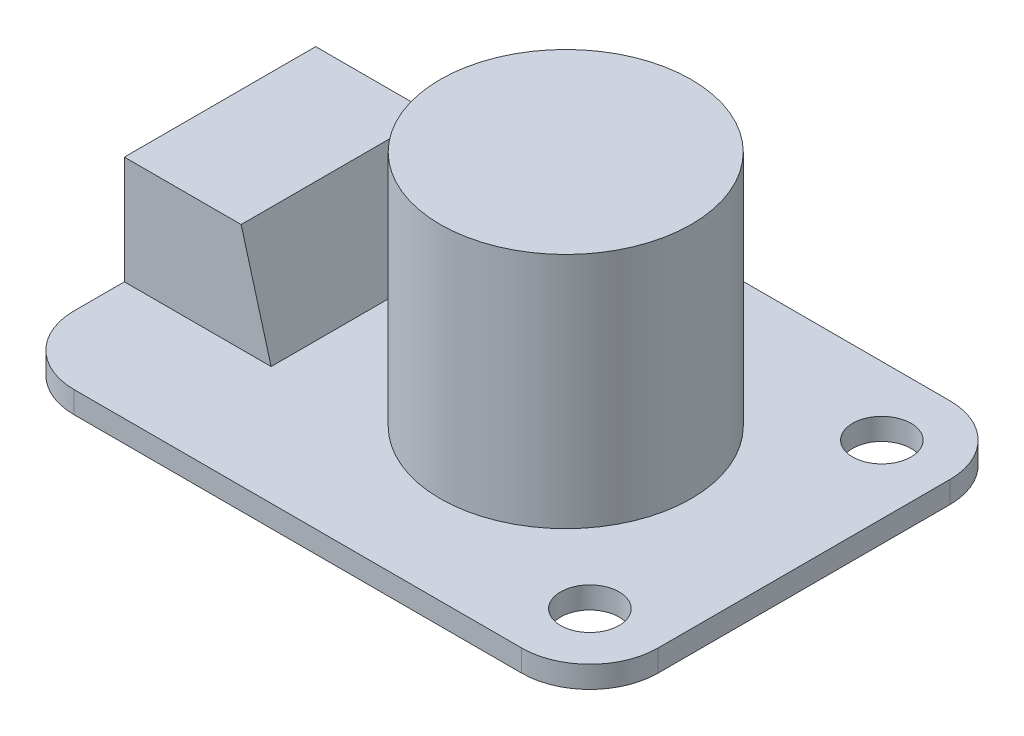
SolidWorks part; units mm, degrees
ref_plane "Front Plane" through (0, 0, 0) normal (0, 0, 1) x (1, 0, 0)
ref_plane "Top Plane" through (0, 0, 0) normal (0, 1, 0) x (1, 0, 0)
ref_plane "Right Plane" through (0, 0, 0) normal (1, 0, 0) x (0, 0, -1)
sketch "Sketch1" plane through (0, 0, 0) normal (0, 1, 0) x (1, 0, 0)
  line L0 (3.5, 0) -> (26.5, 0)
  line L1 (30, 3.5) -> (30, 18.5)
  line L2 (26.5, 22) -> (3.5, 22)
  line L3 (0, 18.5) -> (0, 3.5)
  arc A0 (3.5, 22) -> (0, 18.5) centre (3.5, 18.5) ccw
  arc A1 (3.5, 0) -> (0, 3.5) centre (3.5, 3.5) cw
  arc A2 (26.5, 0) -> (30, 3.5) centre (26.5, 3.5) ccw
  arc A3 (30, 18.5) -> (26.5, 22) centre (26.5, 18.5) ccw
  circle A4 centre (26.5, 18.5) radius 1.5
  circle A5 centre (26.5, 3.5) radius 1.5
  point P9 (0, 0)
  dimension "D3" = 3.5
  dimension "D4" = 3.5
  dimension "D5" = 3.5
  dimension "D6" = 3.5
  dimension "D7" = 3
  dimension "D8" = 3
  dimension "D1" = 30
  dimension "D2" = 22
extrude "Boss-Extrude1" add sketch "Sketch1" along normal blind 1.12
sketch "Sketch2" plane through (0, 1.12, 0) normal (0, 1, 0) x (1, 0, 0)
  line L0 (0, 15.915) -> (0, 6.085)
  line L1 (0, 18.5) -> (0, 3.5) construction
  line L2 (0, 6.085) -> (6, 6.085)
  line L3 (6, 6.085) -> (6, 15.915)
  line L4 (6, 15.915) -> (0, 15.915)
  line L5 (26.5, 22) -> (3.5, 22) construction
  point P4 (0, 11)
  dimension "D1" = 11
  dimension "D2" = 9.83
  dimension "D3" = 6
extrude "Boss-Extrude2" add sketch "Sketch2" along normal blind 5.55
sketch "Sketch3" plane through (0, 0, -6.085) normal (0, 0, 1) x (1, 0, 0)
  line L0 (0, 1.12) -> (7.54, 1.12)
  line L1 (3.5, 1.12) -> (26.5, 1.12) construction
  line L2 (7.54, 1.12) -> (6, 6.67)
  line L3 (6, 6.67) -> (0, 6.67)
  line L4 (0, 6.67) -> (0, 1.12)
  dimension "D1" = 7.54
extrude "Boss-Extrude3" add sketch "Sketch3" against normal blind 9.83
sketch "Sketch4" plane through (0, 1.12, 0) normal (0, 1, 0) x (1, 0, 0)
  line L0 (26.5, 22) -> (3.5, 22) construction
  line L1 (30, 3.5) -> (30, 18.5) construction
  circle A0 centre (17.76, 11) radius 6.45
  dimension "D3" = 12.9
  dimension "D1" = 11
  dimension "D2" = 12.24
extrude "Boss-Extrude4" add sketch "Sketch4" along normal blind 12.2
